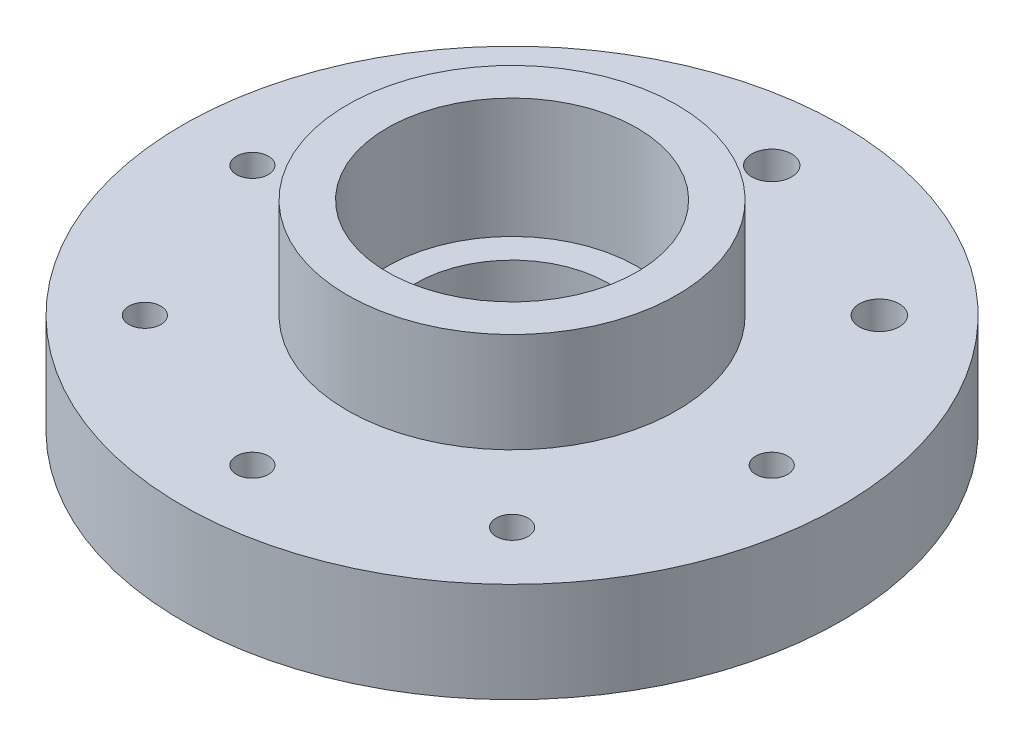
SolidWorks part; units mm, degrees
material "Plain Carbon Steel"
ref_plane "Front Plane" through (0, 0, 0) normal (0, 0, 1) x (1, 0, 0)
ref_plane "Top Plane" through (0, 0, 0) normal (0, 1, 0) x (1, 0, 0)
ref_plane "Right Plane" through (0, 0, 0) normal (1, 0, 0) x (0, 0, -1)
sketch "Sketch1" plane through (0, 0, 0) normal (0, 1, 0) x (1, 0, 0)
  circle A0 centre (0, 0) radius 56 construction
  circle A1 centre (0, 0) radius 82.5 construction
  circle A2 centre (65, 0) radius 4 construction
  circle A3 centre (65, 0) radius 4
  circle A4 centre (45.9619, -45.9619) radius 4 construction
  circle A5 centre (0, -65) radius 4 construction
  circle A6 centre (-45.9619, -45.9619) radius 4 construction
  circle A7 centre (-65, 0) radius 4 construction
  circle A11 centre (45.9619, -45.9619) radius 4
  circle A12 centre (0, -65) radius 4
  circle A13 centre (-45.9619, -45.9619) radius 4
  circle A14 centre (-65, 0) radius 4
  circle A15 centre (-45.9619, 45.9619) radius 5
  circle A16 centre (0, 65) radius 5
  circle A17 centre (45.9619, 45.9619) radius 5
  circle A18 centre (0, 0) radius 55 construction
  circle A19 centre (45.9619, 45.9619) radius 5 construction
  circle A20 centre (0, 65) radius 5 construction
  circle A21 centre (-45.9619, 45.9619) radius 5 construction
  dimension "D1" = 165
  dimension "D2" = 13.5
  dimension "D3" = 1
sketch "Sketch2" plane through (0, 0, 0) normal (0, 0, 1) x (1, 0, 0)
  line L0 (0, 0) -> (0, 67.5538) construction
  line L1 (82.5, 0) -> (56, 0)
  line L2 (82.5, 0) -> (-82.5, 0) construction
  line L3 (56, 0) -> (-56, 0) construction
  line L7 (24, 20) -> (31.2565, 20)
  line L8 (82.5, 25) -> (82.5, 0)
  line L10 (82.5, 25) -> (41.2565, 25)
  line L12 (24, 20) -> (24, 6)
  line L15 (56, 0) -> (56, 6)
  line L16 (56, 6) -> (24, 6)
  line L17 (31.2565, 20) -> (31.2565, 50)
  line L18 (31.2565, 50) -> (41.2565, 50)
  line L20 (41.2565, 25) -> (41.2565, 50)
  dimension "D1" = 50
  dimension "D2" = 20
  dimension "D3" = 6
  dimension "D4" = 112
  dimension "D5" = 62.5129
  dimension "D6" = 48
  dimension "D7" = 10
  dimension "D8" = 14
  dimension "D9" = 25
revolve "Revolve1" add sketch "Sketch2" angle 360 about L0
sketch "Sketch3" plane through (0, 0, 0) normal (0, -1, 0) x (1, 0, 0)
  circle A1 centre (65, 0) radius 4
  circle A2 centre (65, 0) radius 4
  circle A3 centre (45.9619, -45.9619) radius 5
  circle A4 centre (45.9619, -45.9619) radius 5
  circle A5 centre (0, -65) radius 5
  circle A6 centre (0, -65) radius 5
  circle A7 centre (-45.9619, -45.9619) radius 5
  circle A8 centre (-45.9619, -45.9619) radius 5
  circle A9 centre (-65, 0) radius 4
  circle A10 centre (-65, 0) radius 4
  circle A11 centre (-45.9619, 45.9619) radius 4
  circle A12 centre (-45.9619, 45.9619) radius 4
  circle A13 centre (0, 65) radius 4
  circle A14 centre (0, 65) radius 4
  circle A15 centre (45.9619, 45.9619) radius 4
  circle A16 centre (45.9619, 45.9619) radius 4
  dimension "D1" = 0
  dimension "D2" = 0
  dimension "D3" = 0
  dimension "D4" = 0
  dimension "D5" = 0
  dimension "D6" = 0
  dimension "D7" = 0
  dimension "D8" = 0
extrude "Cut-Extrude2" cut sketch "Sketch3" against normal through all
